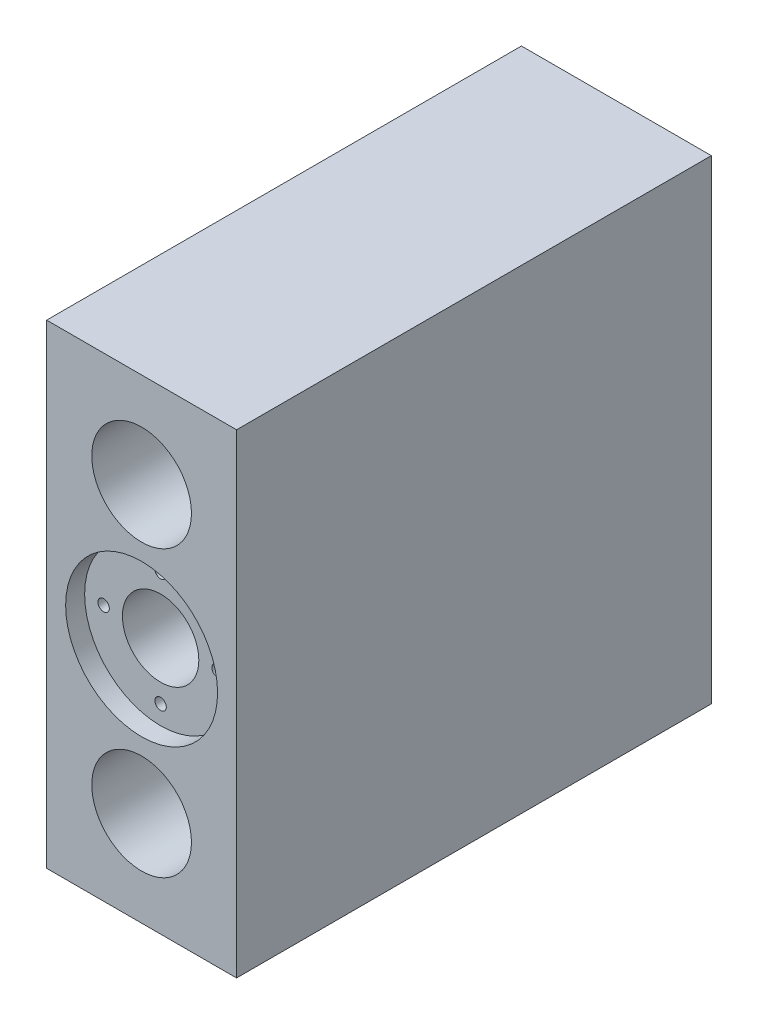
SolidWorks part; units mm, degrees
material "1060 Alloy"
ref_plane "Front Plane" through (0, 0, 0) normal (0, 0, 1) x (1, 0, 0)
ref_plane "Top Plane" through (0, 0, 0) normal (0, 1, 0) x (1, 0, 0)
ref_plane "Right Plane" through (0, 0, 0) normal (1, 0, 0) x (0, 0, -1)
sketch "Sketch2" plane through (0, 0, 0) normal (0, 0, 1) x (1, 0, 0)
  line L0 (20, 0) -> (20, -100) construction
  line L1 (0, 0) -> (40, 0)
  line L2 (0, 0) -> (0, -100)
  line L3 (0, -100) -> (40, -100)
  line L4 (40, 0) -> (40, -100)
  line L5 (20, -20) -> (20, -50) construction
  circle A0 centre (20, -50) radius 5.5
  circle A1 centre (20, -20) radius 10.5
  circle A2 centre (20, -80) radius 10.5
  dimension "D3" = 21
  dimension "D4" = 21
  dimension "D5" = 11
  dimension "D1" = 30
  dimension "D2" = 30
  dimension "D6" = 100
  dimension "D7" = 40
extrude "Boss-Extrude1" add sketch "Sketch2" along normal blind 100
sketch "Sketch3" plane through (0, 0, 100) normal (0, 0, 1) x (1, 0, 0)
  circle A0 centre (20, -50) radius 16
  dimension "D1" = 32
extrude "Cut-Extrude1" cut sketch "Sketch3" against normal blind 4
sketch "Sketch4" plane through (0, 0, 96) normal (0, 0, 1) x (1, 0, 0)
  circle A0 centre (20, -50) radius 8.05
  dimension "D1" = 16.1
extrude "Cut-Extrude2" cut sketch "Sketch4" against normal blind 16
sketch "Sketch5" plane through (0, 0, 96) normal (0, 0, 1) x (1, 0, 0)
  line L1 (20, -38) -> (8, -38) construction
  line L2 (8, -38) -> (8, -50) construction
  line L3 (20, -62) -> (32, -62) construction
  line L4 (32, -62) -> (32, -50) construction
  circle A0 centre (20, -50) radius 12 construction
  circle A1 centre (20, -38) radius 1.2
  circle A2 centre (8, -50) radius 1.2
  circle A3 centre (32, -50) radius 1.2
  circle A4 centre (20, -62) radius 1.2
  dimension "D1" = 24
  dimension "D2" = 2.4
extrude "Cut-Extrude3" cut sketch "Sketch5" against normal blind 15
sketch "Sketch6" plane through (0, 0, 0) normal (0, 0, -1) x (-1, 0, 0)
  circle A0 centre (-20, -50) radius 16
  dimension "D1" = 32
extrude "Cut-Extrude4" cut sketch "Sketch6" against normal blind 4
sketch "Sketch7" plane through (0, 0, 4) normal (0, 0, -1) x (-1, 0, 0)
  circle A0 centre (-20, -50) radius 8.05
  dimension "D1" = 16.1
extrude "Cut-Extrude5" cut sketch "Sketch7" against normal blind 16
sketch "Sketch8" plane through (0, 0, 4) normal (0, 0, -1) x (-1, 0, 0)
  circle A1 centre (-20, -62) radius 1.2
  circle A2 centre (-20, -62) radius 1.2
  circle A3 centre (-32, -50) radius 1.2
  circle A4 centre (-32, -50) radius 1.2
  circle A5 centre (-8, -50) radius 1.2
  circle A6 centre (-8, -50) radius 1.2
  circle A7 centre (-20, -38) radius 1.2
  circle A8 centre (-20, -38) radius 1.2
  dimension "D1" = 0
  dimension "D2" = 0
  dimension "D3" = 0
  dimension "D4" = 0
extrude "Cut-Extrude6" cut sketch "Sketch8" against normal blind 15
